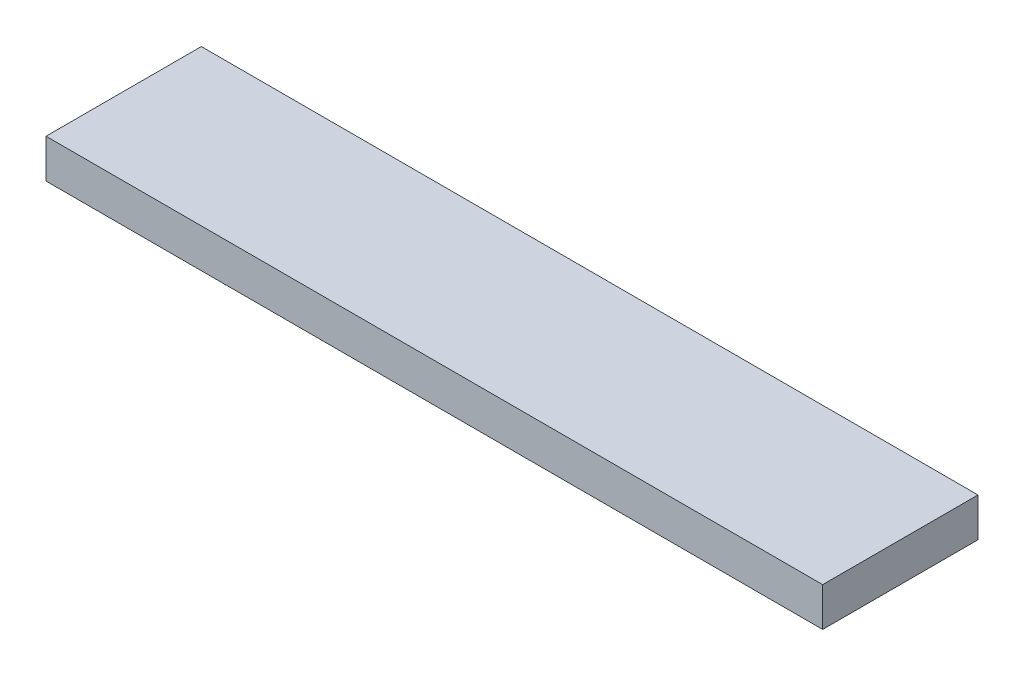
SolidWorks part; units mm, degrees
ref_plane "Front Plane" through (0, 0, 0) normal (0, 0, 1) x (1, 0, 0)
ref_plane "Top Plane" through (0, 0, 0) normal (0, 1, 0) x (1, 0, 0)
ref_plane "Right Plane" through (0, 0, 0) normal (1, 0, 0) x (0, 0, -1)
sketch "Sketch1" plane through (0, 0, 0) normal (0, 1, 0) x (1, 0, 0)
  line L1 (-88.1811, -12.7) -> (38.8189, -12.7)
  line L2 (-88.1811, -12.7) -> (-88.1811, 12.7)
  line L3 (-88.1811, 12.7) -> (38.8189, 12.7)
  line L4 (38.8189, -12.7) -> (38.8189, 12.7)
  dimension "D1" = 25.4
  dimension "D2" = 127
extrude "Boss-Extrude1" add sketch "Sketch1" along normal blind 6.35
